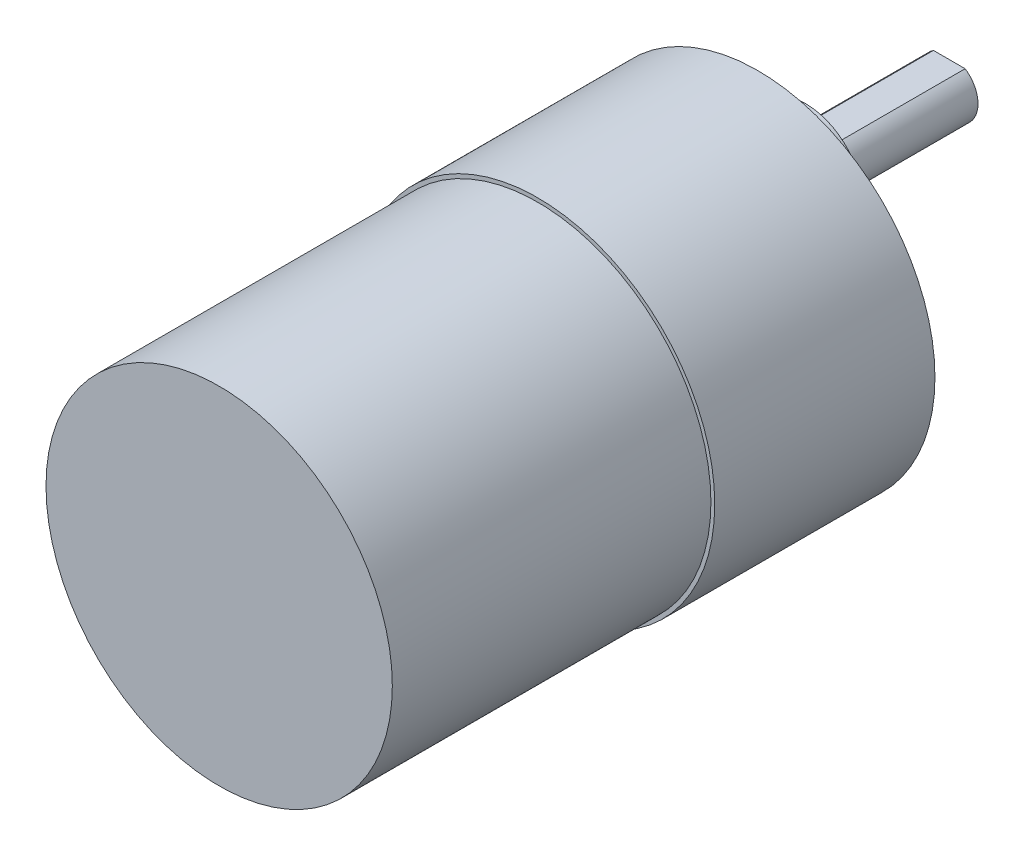
SolidWorks part; units mm, degrees
ref_plane "Front Plane" through (0, 0, 0) normal (0, 0, 1) x (1, 0, 0)
ref_plane "Top Plane" through (0, 0, 0) normal (0, 1, 0) x (1, 0, 0)
ref_plane "Right Plane" through (0, 0, 0) normal (1, 0, 0) x (0, 0, -1)
sketch "Sketch1" plane through (0, 0, 0) normal (0, 0, 1) x (1, 0, 0)
  circle A0 centre (0, 0) radius 18.5
  dimension "D1" = 37
extrude "Boss-Extrude1" add sketch "Sketch1" along normal blind 23.0162
sketch "Sketch2" plane through (0, 0, 23.0162) normal (0, 0, 1) x (1, 0, 0)
  circle A0 centre (0, 0) radius 18.1
  dimension "D1" = 36.2
extrude "Boss-Extrude2" add sketch "Sketch2" along normal blind 33.3
sketch "Sketch3" plane through (0, 0, 0) normal (0, 0, -1) x (-1, 0, 0)
  circle A0 centre (0, 7) radius 6
  dimension "D2" = 12
  dimension "D1" = 7
extrude "Boss-Extrude3" add sketch "Sketch3" along normal blind 5
sketch "Sketch4" plane through (0, 0, -5) normal (0, 0, -1) x (-1, 0, 0)
  arc A0 (-1.6583, 9.5) -> (1.6583, 9.5) centre (0, 7) ccw
  arc A1 (-1.6583, 9.5) -> (1.6583, 9.5) centre (0, 7) cw
  dimension "D1" = 6
extrude "Boss-Extrude4" add sketch "Sketch4" along normal blind 15
sketch "Sketch5" plane through (0, 0, -20) normal (0, 0, -1) x (-1, 0, 0)
  line L0 (-1.6583, 9.5) -> (1.6583, 9.5)
  line L1 (0, 9.5) -> (0, 4) construction
  circle A0 centre (0, 7) radius 3 construction
  circle A1 centre (0, 7) radius 3 construction
  arc A2 (1.6583, 9.5) -> (-1.6583, 9.5) centre (0, 7) ccw
  dimension "D1" = 5.5
extrude "Cut-Extrude1" cut sketch "Sketch5" against normal blind 14
sketch "Sketch6" plane through (0, 0, 0) normal (0, 0, -1) x (-1, 0, 0)
  line L0 (0, 0) -> (0, 15.5) construction
  line L1 (7.75, 13.4234) -> (0, 0) construction
  circle A0 centre (0, 0) radius 15.5 construction
  circle A2 centre (7.75, 13.4234) radius 1.5
  circle A3 centre (15.5, 0) radius 1.5
  circle A4 centre (7.75, -13.4234) radius 1.5
  circle A5 centre (-7.75, -13.4234) radius 1.5
  circle A6 centre (-15.5, 0) radius 1.5
  circle A7 centre (-7.75, 13.4234) radius 1.5
  point P3 (7.75, 13.4234)
  point P14 (0, 0)
  point P21 (0, 0)
  dimension "D1" = 31
  dimension "D3" = 3
  dimension "D2" = 30
  dimension "D4" = 6
extrude "Cut-Extrude2" cut sketch "Sketch6" against normal blind 8
